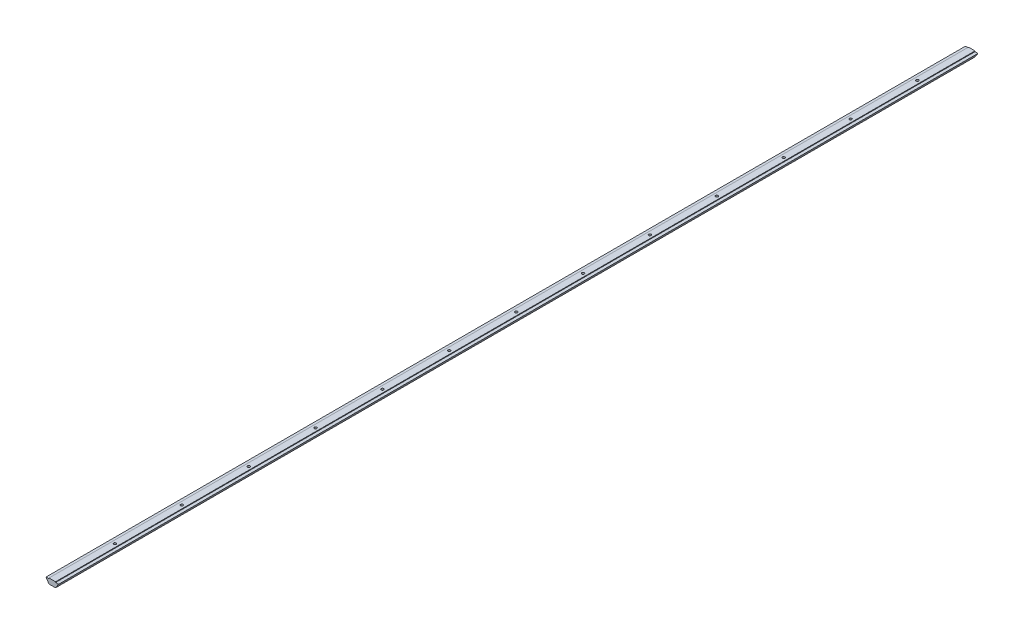
SolidWorks part; units mm, degrees
ref_plane "Front Plane" through (0, 0, 0) normal (0, 0, 1) x (1, 0, 0)
ref_plane "Top Plane" through (0, 0, 0) normal (0, 1, 0) x (1, 0, 0)
ref_plane "Right Plane" through (0, 0, 0) normal (1, 0, 0) x (0, 0, -1)
sketch "Sketch1" plane through (0, 0, 0) normal (0, 0, 1) x (1, 0, 0)
  line L0 (3.9, 0) -> (-3.9, 0)
  line L1 (-3.9, 0) -> (-7.5, 5.5)
  line L2 (-7.5, 5.5) -> (-3.9, 5.5)
  line L3 (-3.9, 5.5) -> (-3.9, 6.3)
  line L4 (-3.9, 6.3) -> (3.9, 6.3)
  line L5 (0, 0) -> (0, 42.4477) construction
  line L6 (3.9, 0) -> (7.5, 5.5)
  line L7 (7.5, 5.5) -> (3.9, 5.5)
  line L8 (3.9, 5.5) -> (3.9, 6.3)
  point P12 (0, 6.3)
  dimension "D1" = 3.9
  dimension "D2" = 7.5
  dimension "D3" = 3.9
  dimension "D4" = 6.3
  dimension "D5" = 5.5
extrude "Boss-Extrude1" add sketch "Sketch1" along normal blind 1100
sketch "Sketch2" plane through (0, 6.3, 0) normal (0, 1, 0) x (1, 0, 0)
  circle A0 centre (0, -65) radius 1.5
  circle A1 centre (0, -145) radius 1.5
  circle A2 centre (0, -225) radius 1.5
  circle A3 centre (0, -305) radius 1.5
  circle A4 centre (0, -385) radius 1.5
  circle A5 centre (0, -465) radius 1.5
  circle A6 centre (0, -545) radius 1.5
  circle A7 centre (0, -625) radius 1.5
  circle A8 centre (0, -705) radius 1.5
  circle A9 centre (0, -785) radius 1.5
  circle A10 centre (0, -865) radius 1.5
  circle A11 centre (0, -945) radius 1.5
  circle A12 centre (0, -1025) radius 1.5
  dimension "D3" = 3
  dimension "D1" = 65
  dimension "D4" = 80
  dimension "D2" = 13
extrude "Cut-Extrude1" cut sketch "Sketch2" against normal through all
